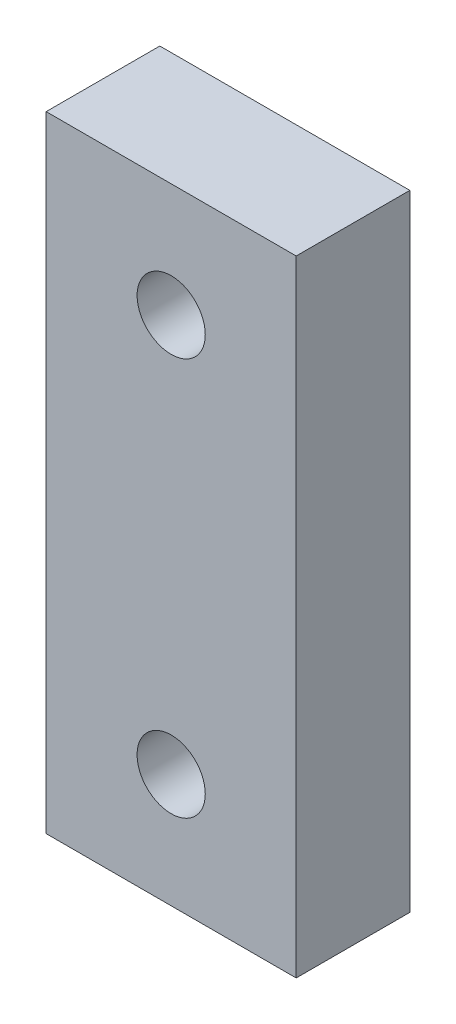
SolidWorks part; units mm, degrees
ref_plane "Front Plane" through (0, 0, 0) normal (0, 0, 1) x (1, 0, 0)
ref_plane "Top Plane" through (0, 0, 0) normal (0, 1, 0) x (1, 0, 0)
ref_plane "Right Plane" through (0, 0, 0) normal (1, 0, 0) x (0, 0, -1)
sketch "Sketch1" plane through (0, 0, 0) normal (0, 0, 1) x (1, 0, 0)
  line L1 (-5.5, 13.755) -> (5.5, 13.755)
  line L2 (-5.5, 13.755) -> (-5.5, -13.755)
  line L3 (-5.5, -13.755) -> (5.5, -13.755)
  line L4 (5.5, 13.755) -> (5.5, -13.755)
  line L5 (-5.5, 13.755) -> (5.5, -13.755) construction
  line L6 (-5.5, -13.755) -> (5.5, 13.755) construction
  point P0 (0, 0)
  dimension "D1" = 27.51
  dimension "D2" = 5.5
extrude "Boss-Extrude2" add sketch "Sketch1" along normal blind 5
sketch "Sketch3" plane through (0, 0, 5) normal (0, 0, 1) x (1, 0, 0)
  line L0 (-5.5, 10.755) -> (5.5, 10.755) construction
  line L1 (-5.5, 13.755) -> (-5.5, -13.755) construction
  line L2 (5.5, -13.755) -> (5.5, 13.755) construction
  line L3 (-5.5, -10.755) -> (5.5, -10.755) construction
  line L4 (0, 13.755) -> (0, -13.755) construction
  line L5 (5.5, 13.755) -> (-5.5, 13.755) construction
  line L6 (-5.5, -13.755) -> (5.5, -13.755) construction
  line L7 (0, 7.255) -> (0, -7.245)
  line L8 (0, 10.255) -> (0, 10.755)
  line L9 (0, -10.245) -> (0, -10.755)
  circle A0 centre (0, 8.755) radius 1.5
  circle A2 centre (0, -8.745) radius 1.5
  line M7 (5.5, -13.755) -> (5.5, 13.755)
  dimension "D3" = 14.5
  dimension "D4" = 3
  dimension "D5" = 3
  dimension "D6" = 0.5
  dimension "D1" = 3
  dimension "D2" = 3
  dimension "D7" = 0.51
extrude "Cut-Extrude1" cut sketch "Sketch3" against normal blind 5 contours A0 | A2 M7
sketch "Sketch4" plane through (0, 0, 0) normal (0, 0, -1) x (-1, 0, 0)
  circle A0 centre (0, 8.755) radius 0.75
  circle A2 centre (0, -8.745) radius 0.75
  circle A3 centre (0, 8.755) radius 1.5
  circle A4 centre (0, -8.745) radius 1.5
  dimension "D1" = 1.5
  dimension "D2" = 1.5
extrude "Boss-Extrude3" add sketch "Sketch4" against normal blind 5
sketch "Sketch6" plane through (0, 0, 0) normal (0, 0, -1) x (-1, 0, 0)
  circle A0 centre (0, 8.755) radius 1.5
  circle A1 centre (0, -8.745) radius 1.5
  dimension "D1" = 3
  dimension "D2" = 3
extrude "Cut-Extrude2" cut sketch "Sketch6" against normal blind 50
